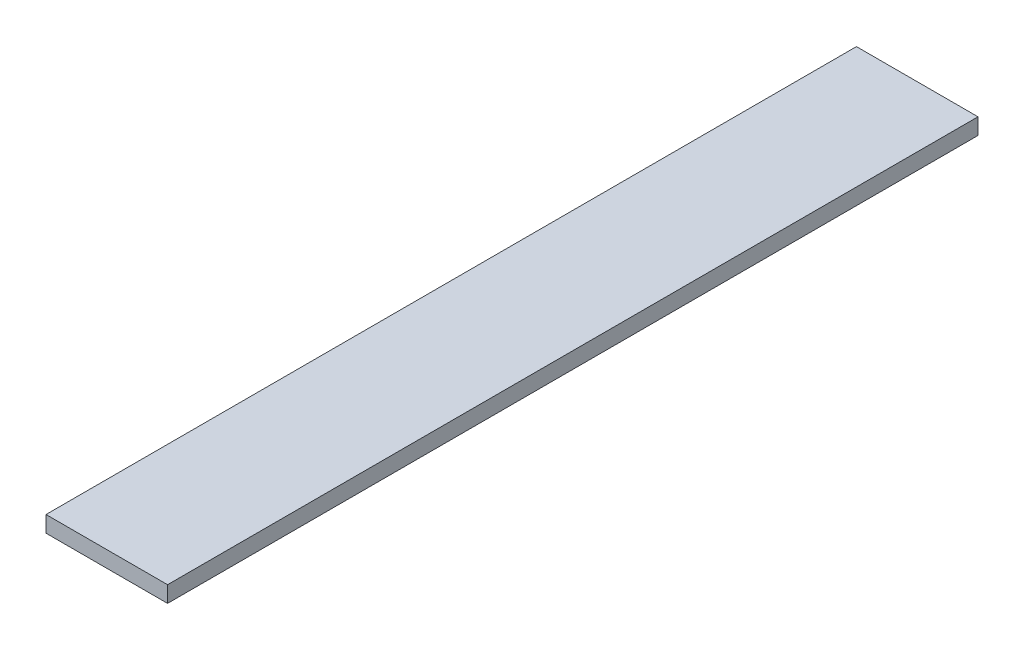
SolidWorks part; units mm, degrees
ref_plane "Front Plane" through (0, 0, 0) normal (0, 0, 1) x (1, 0, 0)
ref_plane "Top Plane" through (0, 0, 0) normal (0, 1, 0) x (1, 0, 0)
ref_plane "Right Plane" through (0, 0, 0) normal (1, 0, 0) x (0, 0, -1)
sketch "Sketch1" plane through (0, 0, 0) normal (0, 0, 1) x (1, 0, 0)
  line L1 (-75, -10) -> (75, -10)
  line L2 (-75, -10) -> (-75, 10)
  line L3 (-75, 10) -> (75, 10)
  line L4 (75, -10) -> (75, 10)
  line L5 (-75, -10) -> (75, 10) construction
  line L6 (-75, 10) -> (75, -10) construction
  point P0 (0, 0)
  dimension "D1" = 150
  dimension "D2" = 20
extrude "Boss-Extrude1" add sketch "Sketch1" along normal mid plane 1000
sketch "Sketch2" plane through (75, 0, 0) normal (1, 0, 0) x (0, 0, -1)
  line L0 (-500, -10) -> (500, -10) construction
  line L1 (-60, 60) -> (60, 60)
  line L2 (-60, 60) -> (-60, -60)
  line L3 (-60, -60) -> (60, -60)
  line L4 (60, 60) -> (60, -60)
  line L5 (-60, 60) -> (60, -60) construction
  line L6 (-60, -60) -> (60, 60) construction
  line L7 (-13, -10) -> (13, -10)
  line L8 (-13, -10) -> (-13, -36)
  line L9 (-13, -36) -> (13, -36)
  line L10 (13, -10) -> (13, -36)
  line L11 (0, -10) -> (0, -36) construction
  line L12 (13, -23) -> (-13, -23) construction
  circle A1 centre (0, -23) radius 18.3848 construction
  circle A2 centre (0, -23) radius 21.3848
  circle A3 centre (0, -23) radius 21.5848
  circle A4 centre (0, -23) radius 24.5848
  point P0 (0, 0)
  point P12 (0, -10)
  dimension "D1" = 120
  dimension "D2" = 120
  dimension "D3" = 26
  dimension "D4" = 3
  dimension "D5" = 0.2
  dimension "D6" = 3
